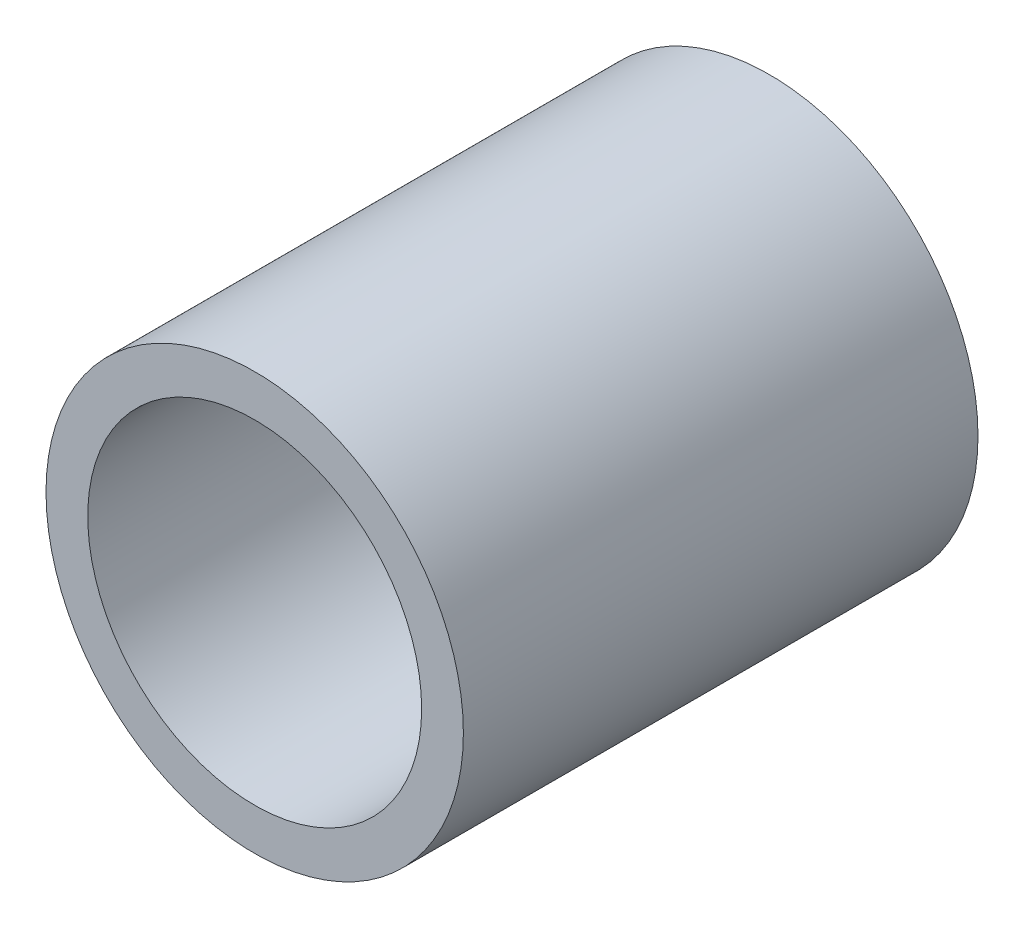
SolidWorks part; units mm, degrees
ref_plane "Front Plane" through (0, 0, 0) normal (0, 0, 1) x (1, 0, 0)
ref_plane "Top Plane" through (0, 0, 0) normal (0, 1, 0) x (1, 0, 0)
ref_plane "Right Plane" through (0, 0, 0) normal (1, 0, 0) x (0, 0, -1)
sketch "Sketch1" plane through (0, 0, 0) normal (0, 0, 1) x (1, 0, 0)
  circle A0 centre (0, 0) radius 6.35
  circle A1 centre (0, 0) radius 7.9375
  dimension "D1" = 15.875
  dimension "D2" = 12.7
extrude "Boss-Extrude1" add sketch "Sketch1" along normal mid plane 19.5728
